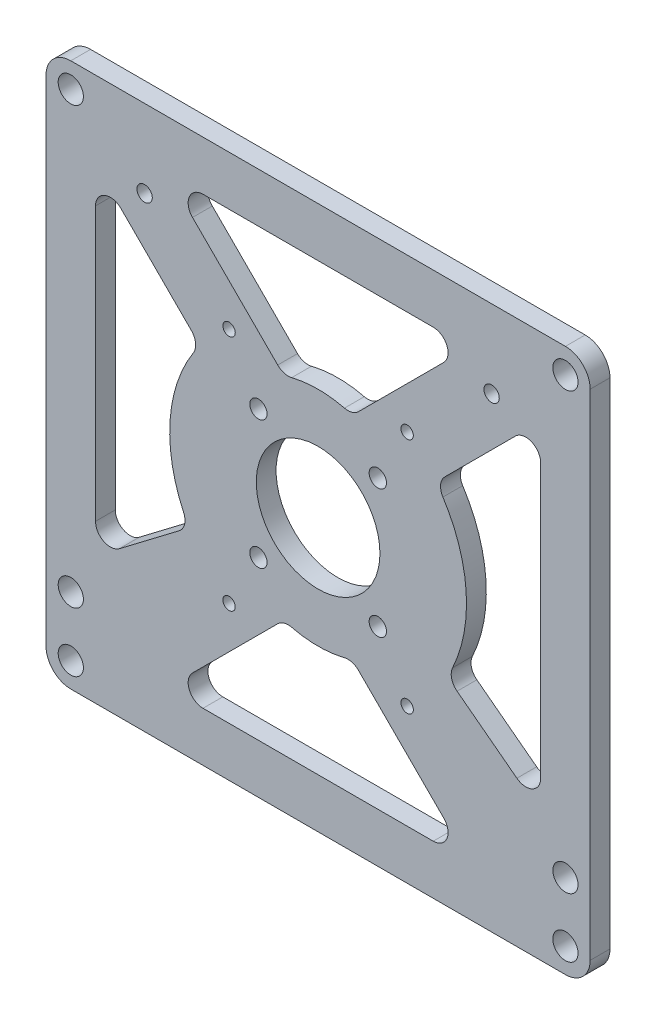
SolidWorks part; units mm, degrees
ref_plane "前视基准面" through (0, 0, 0) normal (0, 0, 1) x (1, 0, 0)
ref_plane "上视基准面" through (0, 0, 0) normal (0, 1, 0) x (1, 0, 0)
ref_plane "右视基准面" through (0, 0, 0) normal (1, 0, 0) x (0, 0, -1)
other "Configuration Table"
ref_plane "基准面1" through (0, 0, 50) normal (0, 0, 1) x (1, 0, 0)
sketch "草图2" plane through (0, 0, 50) normal (0, 0, 1) x (1, 0, 0)
  line L0 (-36.9181, 90.7995) -> (-25.3566, 96.8062)
  line L1 (-38.3947, 89.4801) -> (-45.6586, 78.6642)
  line L2 (-55, 48) -> (-55, 10)
  line L3 (0, 103) -> (0, -7) construction
  line L4 (55, 48) -> (55, 10)
  line L5 (38.3947, 89.4801) -> (45.6586, 78.6642)
  line L6 (36.9181, 90.7995) -> (25.3566, 96.8062)
  line L7 (-43.581, 30.9048) -> (-54.3176, 12.5216)
  line L8 (-50, 5) -> (50, 5)
  line L9 (54.3176, 12.5216) -> (43.581, 30.9048)
  line L10 (40.5902, 41.2759) -> (39.0719, 87.3817)
  line L11 (34.0395, 91.1139) -> (2.5863, 82.6925)
  line L12 (-2.5863, 82.6925) -> (-34.0395, 91.1139)
  line L13 (-39.0719, 87.3817) -> (-40.5902, 41.2759)
  line L14 (-43.581, 30.9048) -> (-54.3176, 12.5216)
  line L15 (-50, 5) -> (50, 5)
  line L16 (54.3176, 12.5216) -> (43.581, 30.9048)
  line L17 (40.5902, 41.2759) -> (39.0719, 87.3817)
  line L18 (34.0395, 91.1139) -> (2.5863, 82.6925)
  line L19 (-2.5863, 82.6925) -> (-34.0395, 91.1139)
  line L20 (-39.0719, 87.3817) -> (-40.5902, 41.2759)
  circle A0 centre (-50, 10) radius 2.55 construction
  circle A1 centre (-50, 10) radius 2.55
  circle A2 centre (50, 10) radius 2.55 construction
  circle A3 centre (50, 10) radius 2.55
  circle A4 centre (35.074, 87.25) radius 1.55 construction
  circle A5 centre (35.074, 87.25) radius 1.55
  circle A6 centre (-35.074, 87.25) radius 1.55 construction
  arc A7 (-43.581, 30.9048) -> (-40.5902, 41.2759) centre (-62.5783, 42) ccw
  arc A8 (-54.3176, 12.5216) -> (-50, 5) centre (-50, 10) ccw
  arc A9 (50, 5) -> (54.3176, 12.5216) centre (50, 10) ccw
  arc A10 (40.5902, 41.2759) -> (43.581, 30.9048) centre (62.5783, 42) ccw
  arc A11 (39.0719, 87.3817) -> (34.0395, 91.1139) centre (35.074, 87.25) ccw
  arc A12 (-2.5863, 82.6925) -> (2.5863, 82.6925) centre (0, 92.3522) ccw
  arc A13 (-34.0395, 91.1139) -> (-39.0719, 87.3817) centre (-35.074, 87.25) ccw
  arc A14 (-43.581, 30.9048) -> (-40.5902, 41.2759) centre (-62.5783, 42) ccw
  arc A15 (-54.3176, 12.5216) -> (-50, 5) centre (-50, 10) ccw
  arc A16 (50, 5) -> (54.3176, 12.5216) centre (50, 10) ccw
  arc A17 (40.5902, 41.2759) -> (43.581, 30.9048) centre (62.5783, 42) ccw
  arc A18 (39.0719, 87.3817) -> (34.0395, 91.1139) centre (35.074, 87.25) ccw
  arc A19 (-2.5863, 82.6925) -> (2.5863, 82.6925) centre (0, 92.3522) ccw
  arc A20 (-34.0395, 91.1139) -> (-39.0719, 87.3817) centre (-35.074, 87.25) ccw
  circle A21 centre (-35.074, 87.25) radius 1.55
  circle A22 centre (-12.07, 61) radius 1.75 construction
  circle A23 centre (-12.07, 61) radius 1.75
  circle A24 centre (12.07, 61) radius 1.75 construction
  circle A25 centre (12.07, 61) radius 1.75
  circle A26 centre (12.07, 35) radius 1.75 construction
  circle A27 centre (12.07, 35) radius 1.75
  circle A28 centre (-12.07, 35) radius 1.75 construction
  circle A29 centre (-12.07, 35) radius 1.75
  circle A30 centre (-18, 72) radius 1.25 construction
  circle A31 centre (-18, 72) radius 1.25
  circle A32 centre (-18, 24) radius 1.25 construction
  circle A33 centre (18, 24) radius 1.25 construction
  circle A34 centre (18, 72) radius 1.25 construction
  circle A35 centre (-18, 24) radius 1.25
  circle A36 centre (18, 24) radius 1.25
  circle A37 centre (18, 72) radius 1.25
  circle A38 centre (0, 48) radius 55
  dimension "D2" = 110
  dimension "D1" = 0
extrude "凸台-拉伸1" add sketch "草图2" along normal blind 4 contours L3 A38 L19 A19 | A38 L0 A20 L19 | A38 L19 A20 L20 A21 | L3 A19 L19 A38 L20 A14 L14 L15 A35 A31 A29 A23 | A38 L20 A20 L1 | L20 A38 L14 A14 | A38 L2 A15 L14 | A38 L14 A15 L15 A1 | L3 L15 A38 | L15 L3 A38 | A19 L3 L15 A38 L16 A17 L17 L18 A25 A27 A36 A37 | A38 L15 A16 L16 A3 | A38 L16 A16 L4 | A38 L17 A17 L16 | A38 L5 A18 L17 | A38 L17 A18 L18 A5 | A38 L18 A18 L6 | A38 L3 A19 L18
fillet "圆角1" radius 20 2 edges at (-34.2929, 5, 52) (34.2929, 5, 52)
sketch "草图3" plane through (0, 0, 54) normal (0, 0, 1) x (1, 0, 0)
  line L0 (18, 72) -> (-18, 24) construction
  circle A0 centre (0, 48) radius 50
  circle A1 centre (0, 48) radius 44
  circle A3 centre (0, 92) radius 1.75
  circle A4 centre (38.1051, 70) radius 1.75
  circle A5 centre (38.1051, 26) radius 1.75
  circle A6 centre (0, 4) radius 1.75
  circle A7 centre (-38.1051, 26) radius 1.75
  circle A8 centre (-38.1051, 70) radius 1.75
  point P20 (0, 48)
  dimension "D1" = 100
  dimension "D2" = 88
  dimension "D3" = 3.5
  dimension "D4" = 6
sketch "草图4" plane through (0, 0, 54) normal (0, 0, 1) x (1, 0, 0)
  circle A0 centre (0, 48) radius 12.5
  dimension "D1" = 25
extrude "切除-拉伸3" cut sketch "草图4" against normal blind 4
sketch "草图8" plane through (0, 0, 54) normal (0, 0, 1) x (1, 0, 0)
  line L0 (-55, 48) -> (-55, 103)
  line L1 (-55, 103) -> (0, 103)
  line L10 (-50, 5) -> (-40.694, 5)
  line L11 (40.694, 5) -> (50, 5)
  line L12 (55, 10) -> (55, 48)
  line L13 (45.6586, 78.6642) -> (38.3947, 89.4801)
  line L14 (36.9181, 90.7995) -> (25.3566, 96.8062)
  line L15 (-25.3566, 96.8062) -> (-36.9181, 90.7995)
  line L16 (-38.3947, 89.4801) -> (-45.6586, 78.6642)
  line L17 (-55, 48) -> (-55, 10)
  line L18 (-50, 5) -> (-40.694, 5)
  line L19 (40.694, 5) -> (50, 5)
  line L20 (55, 10) -> (55, 48)
  line L21 (45.6586, 78.6642) -> (38.3947, 89.4801)
  line L22 (36.9181, 90.7995) -> (25.3566, 96.8062)
  line L23 (-25.3566, 96.8062) -> (-36.9181, 90.7995)
  line L24 (-38.3947, 89.4801) -> (-45.6586, 78.6642)
  line L25 (-55, 48) -> (-55, 10)
  arc A0 (25.3566, 96.8062) -> (-25.3566, 96.8062) centre (0, 48) ccw construction
  arc A11 (-29.8423, 1.8) -> (-40.694, 5) centre (-40.694, -15) ccw
  arc A12 (-29.8423, 1.8) -> (29.8423, 1.8) centre (0, 48) ccw
  arc A13 (40.694, 5) -> (29.8423, 1.8) centre (40.694, -15) ccw
  arc A14 (50, 5) -> (55, 10) centre (50, 10) ccw
  arc A15 (55, 48) -> (45.6586, 78.6642) centre (0, 48) ccw
  arc A16 (38.3947, 89.4801) -> (36.9181, 90.7995) centre (35.074, 87.25) ccw
  arc A17 (25.3566, 96.8062) -> (-25.3566, 96.8062) centre (0, 48) ccw
  arc A18 (-36.9181, 90.7995) -> (-38.3947, 89.4801) centre (-35.074, 87.25) ccw
  arc A19 (-45.6586, 78.6642) -> (-55, 48) centre (0, 48) ccw
  arc A20 (-55, 10) -> (-50, 5) centre (-50, 10) ccw
  arc A21 (-29.8423, 1.8) -> (-40.694, 5) centre (-40.694, -15) ccw
  arc A22 (-29.8423, 1.8) -> (29.8423, 1.8) centre (0, 48) ccw
  arc A23 (40.694, 5) -> (29.8423, 1.8) centre (40.694, -15) ccw
  arc A24 (50, 5) -> (55, 10) centre (50, 10) ccw
  arc A25 (55, 48) -> (45.6586, 78.6642) centre (0, 48) ccw
  arc A26 (38.3947, 89.4801) -> (36.9181, 90.7995) centre (35.074, 87.25) ccw
  arc A27 (25.3566, 96.8062) -> (-25.3566, 96.8062) centre (0, 48) ccw
  arc A28 (-36.9181, 90.7995) -> (-38.3947, 89.4801) centre (-35.074, 87.25) ccw
  arc A29 (-45.6586, 78.6642) -> (-55, 48) centre (0, 48) ccw
  arc A30 (-55, 10) -> (-50, 5) centre (-50, 10) ccw
  dimension "D1" = 0
extrude "凸台-拉伸2" add sketch "草图8" against normal blind 4 contours A29 L24 A28 L23 A27 L1 L0
mirror "镜向4" about plane through (0, 0, 0) normal (1, 0, 0) of "凸台-拉伸2"
fillet "圆角5" radius 5 2 edges at (-55, 103, 52) (55, 103, 52)
sketch "草图10" plane through (0, 0, 54) normal (0, 0, 1) x (1, 0, 0)
  circle A0 centre (-50, 98) radius 2.55
  circle A1 centre (50, 98) radius 2.55
  dimension "D1" = 5.1
  dimension "D2" = 5.1
extrude "切除-拉伸6" cut sketch "草图10" against normal blind 10
sketch "草图11" plane through (0, 0, 50) normal (0, 0, -1) x (-1, 0, 0)
  line L0 (-55, 13.7579) -> (-55, -7)
  line L1 (-55, 98) -> (-55, 10) construction
  line L2 (-55, -7) -> (55, -7)
  line L3 (55, -7) -> (55, 10)
  line L4 (50, 5) -> (40.694, 5) construction
  line L5 (50, 5) -> (40.694, 5)
  line L6 (-40.694, 5) -> (-50, 5) construction
  line L7 (-40.694, 5) -> (-50, 5)
  arc A0 (-29.8423, 1.8) -> (29.8423, 1.8) centre (0, 48) ccw construction
  arc A1 (-29.8423, 1.8) -> (29.8423, 1.8) centre (0, 48) ccw
  arc A2 (40.694, 5) -> (29.8423, 1.8) centre (40.694, -15) ccw construction
  arc A3 (40.694, 5) -> (29.8423, 1.8) centre (40.694, -15) ccw
  arc A4 (50, 5) -> (55, 10) centre (50, 10) ccw construction
  arc A5 (50, 5) -> (55, 10) centre (50, 10) ccw
  arc A6 (-55, 10) -> (-50, 5) centre (-50, 10) ccw construction
  arc A7 (-55, 10) -> (-50, 5) centre (-50, 10) ccw
  arc A8 (-29.8423, 1.8) -> (-40.694, 5) centre (-40.694, -15) ccw construction
  arc A9 (-29.8423, 1.8) -> (-40.694, 5) centre (-40.694, -15) ccw
extrude "凸台-拉伸3" add sketch "草图11" against normal blind 4 contours A1 A9 L7 A7 L0 L2 | A5 L5 A3 A1 L2 L3
fillet "圆角6" radius 5 2 edges at (-55, -7, 52) (55, -7, 52)
sketch "草图12" plane through (0, 0, 50) normal (0, 0, -1) x (-1, 0, 0)
  circle A0 centre (-50, -2) radius 2.55
  circle A1 centre (50, -2) radius 2.55
  dimension "D1" = 5.1
  dimension "D2" = 5.1
extrude "切除-拉伸7" cut sketch "草图12" against normal blind 4
sketch "草图13" plane through (0, 0, 54) normal (0, 0, 1) x (1, 0, 0)
  line L0 (-50, 98) -> (0, 48) construction
  line L1 (0, 48) -> (50, 98) construction
  line L2 (50, -2) -> (0, 48) construction
  line L3 (0, 48) -> (-50, -2) construction
  line L4 (-50, 10) -> (0, 48) construction
  line L5 (0, 48) -> (50, 10) construction
  line L6 (-35.074, 87.25) -> (0, 48) construction
  line L7 (0, 48) -> (35.074, 87.25) construction
  line L8 (-45, 87.3431) -> (-23.8522, 66.1954)
  line L9 (-45, 87.3431) -> (-45, 18.8241)
  line L10 (-45, 18.8241) -> (-26.0919, 33.1942)
  line L11 (0, 103) -> (0, 48) construction
  line L12 (-50, 103) -> (50, 103) construction
  line L13 (-30.5147, 93) -> (0, 93)
  line L14 (0, 93) -> (0, 62.4853)
  line L15 (0, 62.4853) -> (-30.5147, 93)
  line L17 (-55, 98) -> (-55, -2) construction
  line L18 (-22.5, 48) -> (30, 48) construction
  line L19 (0, 3) -> (0, 33.5147)
  line L20 (-30.5147, 3) -> (0, 3)
  line L21 (0, 33.5147) -> (-30.5147, 3)
  circle A0 centre (0, 48) radius 30
  circle A1 centre (0, 48) radius 22.5
  circle A2 centre (-18, 72) radius 1.25 construction
  dimension "D1" = 60
  dimension "D2" = 45
  dimension "D3" = 10
  dimension "D4" = 10
  dimension "D5" = 4
  dimension "D6" = 4
  dimension "D7" = 6
extrude "切除-拉伸8" cut sketch "草图13" against normal blind 4 contours A0 L8 L9 L10 | A0 L14 L13 L15 | A1 L14 A0 L15 | A0 L21 L20 L19 | A1 L21 A0 L19
mirror "镜向5" about plane through (0, 0, 0) normal (1, 0, 0) of "切除-拉伸8"
fillet "圆角7" radius 3 16 edges at (-30.5147, 93, 52) (30.5147, 93, 52) (6.9231, 69.4084, 52) (-6.9231, 69.4084, 52) (45, 87.3431, 52) (45, 18.8241, 52) (23.8522, 66.1954, 52) (26.0919, 33.1942, 52) (6.9231, 26.5916, 52) (30.5147, 3, 52) (-6.9231, 26.5916, 52) (-30.5147, 3, 52) (-45, 87.3431, 52) (-23.8522, 66.1954, 52) (-26.0919, 33.1942, 52) (-45, 18.8241, 52)
